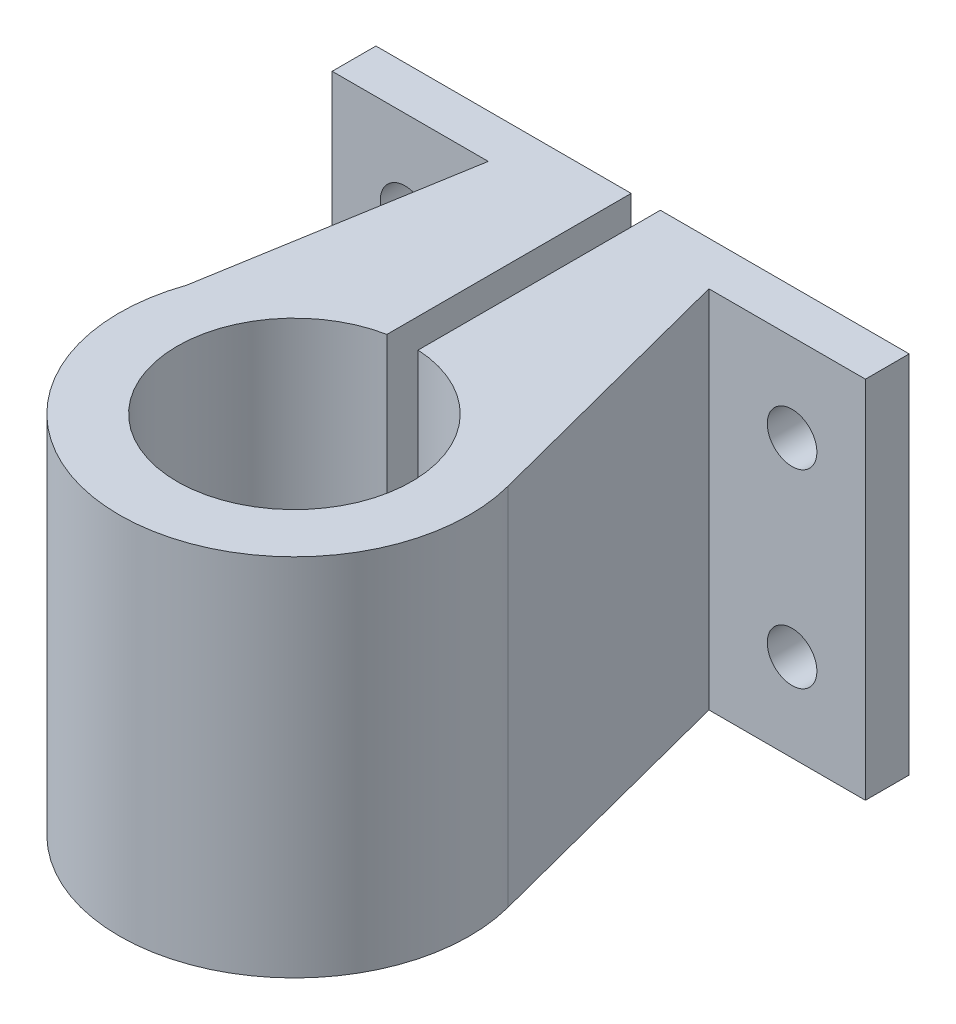
SolidWorks part; units mm, degrees
material "Custom Plastic"
ref_plane "Front Plane" through (0, 0, 0) normal (0, 0, 1) x (1, 0, 0)
ref_plane "Top Plane" through (0, 0, 0) normal (0, 1, 0) x (1, 0, 0)
ref_plane "Right Plane" through (0, 0, 0) normal (1, 0, 0) x (0, 0, -1)
sketch "Sketch1" plane through (0, 0, 0) normal (0, 0, 1) x (1, 0, 0)
  line L0 (-225.5738, 210.9236) -> (-225.5738, 235.9236) construction
  line L2 (-194.0238, 223.4236) -> (-199.0505, 223.4236)
  line L3 (-230.5738, 235.9236) -> (-194.0238, 235.9236)
  line L4 (-264.0238, 235.9236) -> (-264.0238, 210.9236)
  line L5 (-264.0238, 210.9236) -> (40.7762, 210.9236)
  line L6 (40.7762, 210.9236) -> (40.7762, 235.9236)
  line L7 (40.7762, 235.9236) -> (-264.0238, 235.9236)
  line L8 (-264.0238, 235.9236) -> (-264.0238, 210.9236)
  line L9 (-264.0238, 210.9236) -> (40.7762, 210.9236)
  line L10 (40.7762, 210.9236) -> (40.7762, 235.9236)
  line L11 (40.7762, 235.9236) -> (-264.0238, 235.9236)
  line L12 (-230.5738, 235.9236) -> (-230.5738, 210.9236)
  line L13 (-230.5738, 210.9236) -> (-194.0238, 210.9236)
  line L14 (-194.0238, 235.9236) -> (-194.0238, 210.9236)
  line L15 (-199.0505, 223.4236) -> (-199.0505, 50223.4236) construction
  line L16 (-219.4971, 257.8462) -> (-219.4971, 247.8462) construction
  line L17 (-219.4971, 247.8462) -> (-229.0238, 247.8462) construction
  line L18 (-229.0238, 247.8462) -> (-229.0238, 257.8462) construction
  line L19 (-229.0238, 257.8462) -> (-219.4971, 257.8462) construction
  line L20 (-194.0238, 247.8462) -> (-203.4971, 247.8462) construction
  line L21 (-203.4971, 247.8462) -> (-203.4971, 257.8462) construction
  line L22 (-203.4971, 257.8462) -> (-194.0238, 257.8462) construction
  line L23 (-194.0238, 257.8462) -> (-194.0238, 247.8462) construction
  line L24 (-219.4971, 257.8462) -> (-219.4971, 247.8462)
  line L25 (-219.4971, 247.8462) -> (-229.0238, 247.8462)
  line L26 (-229.0238, 247.8462) -> (-229.0238, 257.8462)
  line L27 (-229.0238, 257.8462) -> (-219.4971, 257.8462)
  line L28 (-194.0238, 247.8462) -> (-203.4971, 247.8462)
  line L29 (-203.4971, 247.8462) -> (-203.4971, 257.8462)
  line L30 (-203.4971, 257.8462) -> (-194.0238, 257.8462)
  line L31 (-194.0238, 257.8462) -> (-194.0238, 247.8462)
  circle A0 centre (-225.5738, 216.9236) radius 1.7 construction
  circle A1 centre (-225.5738, 229.9236) radius 1.7 construction
  circle A2 centre (-225.5738, 216.9236) radius 1.7
  circle A3 centre (-225.5738, 229.9236) radius 1.7
  dimension "D1" = 0
extrude "Boss-Extrude1" add sketch "Sketch1" along normal blind 38
sketch "Sketch2" plane through (0, 235.9236, 0) normal (0, 1, 0) x (1, 0, 0)
  line L0 (-211.5311, -24.63) -> (-211.0784, -24.63)
  line L1 (-211.0784, -24.63) -> (-211.5311, -24.63)
  line L2 (-230.5738, 0) -> (-194.0238, 0) construction
  line L3 (-213.0784, -24.63) -> (-211.0784, -24.63)
  line L4 (-213.0784, -16.7421) -> (-213.0784, 0)
  line L5 (-213.0784, 0) -> (-211.0784, 0)
  line L6 (-211.0784, -16.6045) -> (-211.0784, 0)
  line L7 (-223.8738, 0) -> (-227.2738, 0) construction
  line L8 (-223.8738, 0) -> (-227.2738, 0)
  line L11 (-194.0238, 0) -> (-230.5738, 0)
  line L12 (-230.5738, 0) -> (-230.5738, -38)
  line L13 (-230.5738, -38) -> (-194.0238, -38)
  line L14 (-194.0238, -38) -> (-194.0238, 0)
  line L16 (-230.5738, 0) -> (-230.5738, -38)
  line L17 (-230.5738, -38) -> (-194.0238, -38)
  line L18 (-194.0238, -38) -> (-194.0238, 0)
  line L19 (-223.8738, 0) -> (-219.8738, 0)
  line L20 (-200.7505, 0) -> (-204.7505, 0)
  line L21 (-219.8738, -3) -> (-223.5311, -24.63)
  line L22 (-230.5738, 0) -> (-219.8738, 0)
  line L23 (-230.5738, 0) -> (-230.5738, -3)
  line L26 (-204.7505, 0) -> (-194.0238, 0)
  line L29 (-194.0238, 0) -> (-194.0238, -3)
  line L30 (-204.7505, -3) -> (-199.9164, -21.6136)
  line L31 (-230.5738, -3) -> (-219.8738, -3)
  line L32 (-204.7505, -3) -> (-194.0238, -3)
  arc A0 (-213.0784, -16.7421) -> (-211.0784, -16.6045) centre (-211.5311, -24.63) ccw
  arc A1 (-213.0784, -12.7302) -> (-211.0784, -12.6385) centre (-211.5311, -24.63) ccw
  dimension "D1" = 0
extrude "Cut-Extrude1" cut sketch "Sketch2" against normal blind 38
sketch "Sketch3" plane through (0, 0, 0) normal (0, 0, -1) x (-1, 0, 0)
  line L0 (194.0238, 216.9236) -> (199.0505, 216.9236) construction
  line L1 (194.0238, 229.9236) -> (199.0505, 229.9236) construction
  line L4 (194.0238, 210.9236) -> (211.0784, 210.9236)
  line L5 (211.0784, 210.9236) -> (211.0784, 235.9236)
  line L6 (211.0784, 235.9236) -> (194.0238, 235.9236)
  line L7 (194.0238, 235.9236) -> (194.0238, 210.9236)
  line L8 (194.0238, 210.9236) -> (211.0784, 210.9236)
  line L10 (211.0784, 235.9236) -> (194.0238, 235.9236)
  line L11 (194.0238, 235.9236) -> (194.0238, 210.9236)
  line L17 (211.0784, 210.9236) -> (211.0784, 235.9236)
  circle A0 centre (225.5738, 229.9236) radius 1.7 construction
  circle A1 centre (225.5738, 216.9236) radius 1.7 construction
  circle A2 centre (225.5738, 229.9236) radius 1.7
  circle A3 centre (225.5738, 216.9236) radius 1.7
  circle A4 centre (199.0505, 216.9236) radius 1.7
  circle A5 centre (199.0505, 229.9236) radius 1.7
  dimension "D1" = 0
extrude "Cut-Extrude2" cut sketch "Sketch3" against normal blind 9 contours A4 | A5
